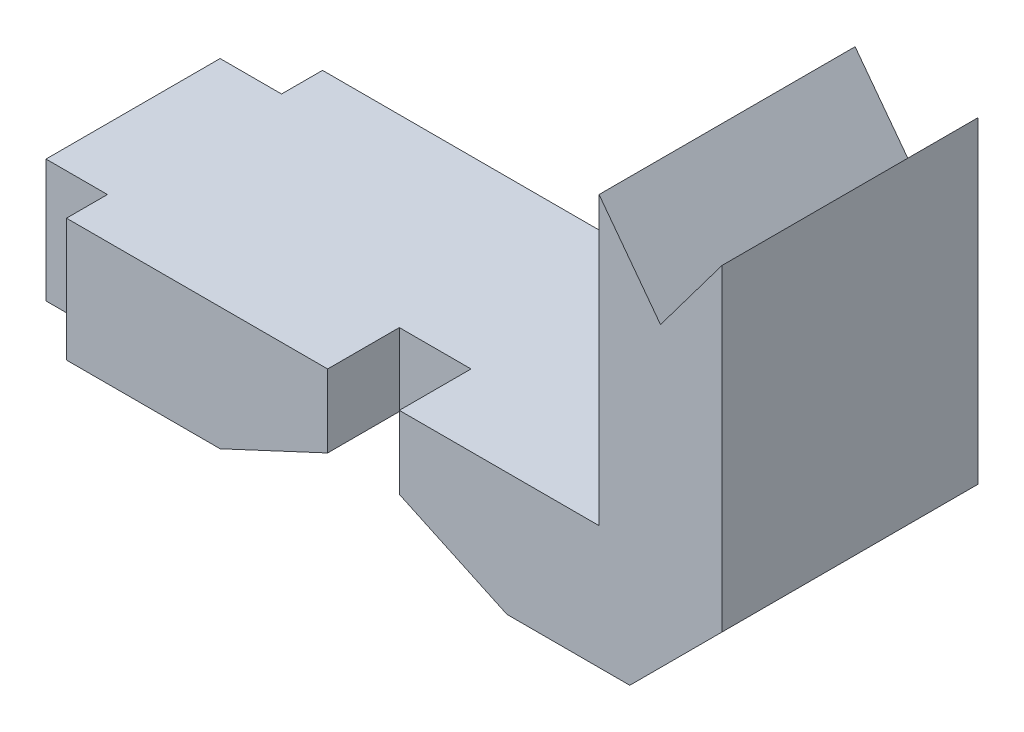
SolidWorks part; units mm, degrees
ref_plane "Спереди" through (0, 0, 0) normal (0, 0, 1) x (1, 0, 0)
ref_plane "Сверху" through (0, 0, 0) normal (0, 1, 0) x (1, 0, 0)
ref_plane "Справа" through (0, 0, 0) normal (1, 0, 0) x (0, 0, -1)
sketch "Эскиз1" plane through (0, 0, 0) normal (0, 0, 1) x (1, 0, 0)
  line L0 (-35, -8) -> (23, -8)
  line L1 (-35, -20) -> (35, -20)
  line L2 (-35, -20) -> (-35, 20)
  line L3 (-35, 20) -> (35, 20)
  line L4 (35, -20) -> (35, 20)
  line L5 (-35, -20) -> (35, 20) construction
  line L6 (-35, 20) -> (35, -20) construction
  line L7 (23, -8) -> (23, 20)
  point P0 (0, 0)
  dimension "D1" = 40
  dimension "D2" = 70
  dimension "D3" = 12
extrude "Бобышка-Вытянуть1" add sketch "Эскиз1" along normal blind 25 contours L7 L0 L2 L1 L4 L3
sketch "Эскиз2" plane through (0, 0, 25) normal (0, 0, 1) x (1, 0, 0)
  line L0 (29, 20) -> (29, -20) construction
  line L1 (23, 20) -> (35, 20) construction
  line L2 (-35, -20) -> (35, -20) construction
  line L3 (23, 20) -> (29, 12)
  line L4 (29, 12) -> (35, 20)
  line L5 (26, -20) -> (35, -11)
  line L6 (35, -20) -> (35, 20) construction
  line L7 (35, -11) -> (35, -20)
  line L8 (35, -20) -> (26, -20)
  line L9 (0, -20) -> (0, -8) construction
  line L10 (-35, -8) -> (23, -8) construction
  line L11 (0, -13.4717) -> (14, -20)
  line L12 (14, -20) -> (-14, -20)
  line L13 (0, -13.4717) -> (-14, -20)
  line M4 (-35, -20) -> (35, -20)
  line M5 (35, -20) -> (35, 20)
  line M6 (35, 20) -> (23, 20)
  dimension "D1" = 8
  dimension "D2" = 45
  dimension "D3" = 9
  dimension "D4" = 25
  dimension "D5" = 14
extrude "Вырез-Вытянуть1" cut sketch "Эскиз2" against normal through all contours L5 M4 M5 | L11 L13 M4 | L3 L4 M6
sketch "Эскиз3" plane through (0, -8, 0) normal (0, 1, 0) x (1, 0, 0)
  line L0 (0, 0) -> (0, -25) construction
  line L1 (-35, -25) -> (-29, -25)
  line L2 (-35, -25) -> (-35, -21)
  line L3 (-35, -21) -> (-29, -21)
  line L4 (-29, -25) -> (-29, -21)
  line L5 (-35, 0) -> (-29, 0)
  line L6 (-35, 0) -> (-35, -4)
  line L7 (-35, -4) -> (-29, -4)
  line L8 (-29, 0) -> (-29, -4)
  line L9 (-35, -25) -> (23, -25) construction
  line L10 (-3.5, -25) -> (3.5, -25)
  line L11 (-3.5, -25) -> (-3.5, -18)
  line L12 (-3.5, -18) -> (3.5, -18)
  line L13 (3.5, -25) -> (3.5, -18)
  line L14 (-3.5, -25) -> (3.5, -18) construction
  line L15 (-3.5, -18) -> (3.5, -25) construction
  point P14 (0, -21.5)
  dimension "D1" = 4
  dimension "D2" = 7
  dimension "D3" = 6
extrude "Вырез-Вытянуть2" cut sketch "Эскиз3" against normal through all
